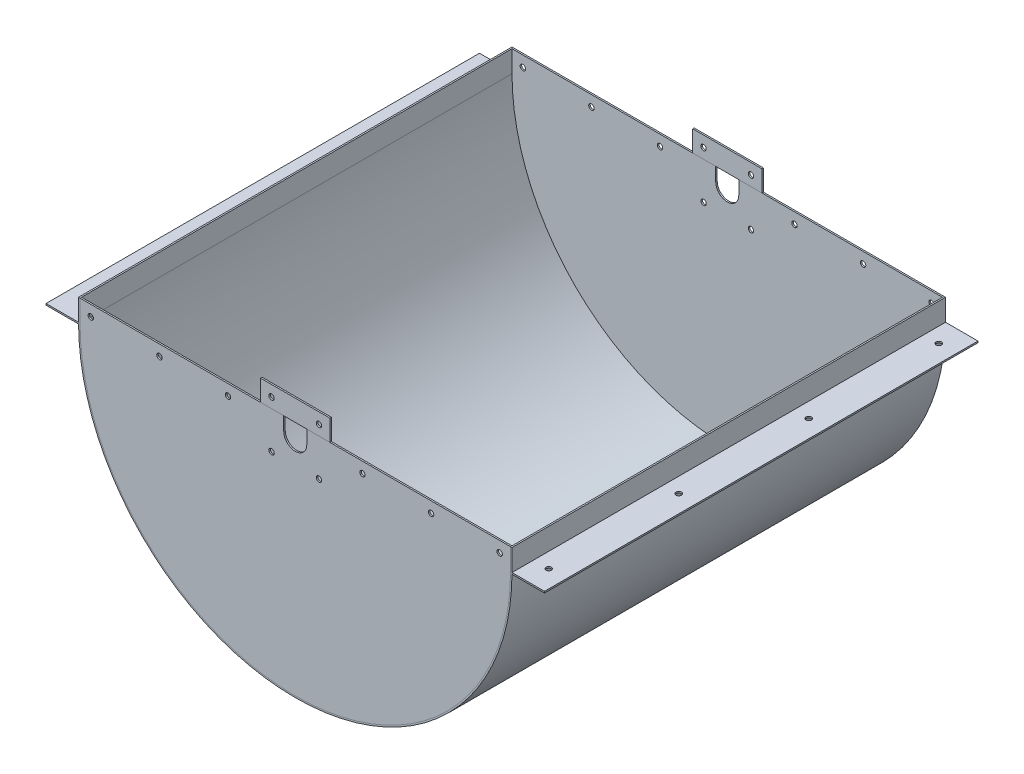
SolidWorks part; units mm, degrees
ref_plane "Plano frontal" through (0, 0, 0) normal (0, 0, 1) x (1, 0, 0)
ref_plane "Plano superior" through (0, 0, 0) normal (0, 1, 0) x (1, 0, 0)
ref_plane "Plano direito" through (0, 0, 0) normal (1, 0, 0) x (0, 0, -1)
sketch "Esboço1" plane through (0, 0, 0) normal (0, 0, 1) x (1, 0, 0)
  line L0 (0, 0) -> (-744.798, 0) construction
  line L1 (0, 0) -> (688.7199, 0) construction
  line L2 (-504.5, 0) -> (-504.5, 50.8)
  line L3 (-504.5, 50.8) -> (-508, 50.8)
  line L4 (-508, 0) -> (-508, 50.8)
  line L5 (0, 0) -> (0, 320.7839) construction
  line L6 (508, 0) -> (508, 50.8)
  line L7 (504.5, 50.8) -> (508, 50.8)
  line L8 (504.5, 0) -> (504.5, 50.8)
  arc A0 (-508, 0) -> (508, 0) centre (0, 0) ccw
  arc A1 (-504.5, 0) -> (504.5, 0) centre (0, 0) ccw
  circle A2 centre (0, 0) radius 508 construction
  circle A3 centre (0, 0) radius 504.5 construction
  dimension "D1" = 1016
  dimension "D3" = 50.8
  dimension "D2" = 3.5
extrude "Ressalto-extrusão1" add sketch "Esboço1" along normal mid plane 1016
sketch "Esboço2" plane through (0, 0, 508) normal (0, 0, 1) x (1, 0, 0)
  line L0 (504.5, 50.8) -> (504.5, 0) construction
  line L1 (-504.5, 0) -> (-504.5, 50.8) construction
  line L2 (504.5, 50.8) -> (504.5, 0)
  line L3 (-504.5, 0) -> (-504.5, 50.8)
  line L4 (-504.5, 50.8) -> (504.5, 50.8)
  arc A0 (-504.5, 0) -> (504.5, 0) centre (0, 0) ccw construction
  arc A1 (-504.5, 0) -> (504.5, 0) centre (0, 0) ccw
extrude "Ressalto-extrusão2" add sketch "Esboço2" against normal blind 3.5 separate body
sketch "Esboço3" plane through (0, 0, 508) normal (0, 0, 1) x (1, 0, 0)
  line L0 (-504.5, 25.4) -> (504.5, 25.4) construction
  line L1 (-504.5, 50.8) -> (-504.5, 0) construction
  line L2 (504.5, 50.8) -> (504.5, 0) construction
  line L3 (504.5, 50.8) -> (-504.5, 50.8) construction
  line L4 (0, 0) -> (0, 166.7118) construction
  line L5 (-504.5, 0) -> (504.5, 0) construction
  line L6 (27, 19.05) -> (27, 50.8)
  line L7 (-27, 19.05) -> (-27, 50.8)
  line L8 (-27, 50.8) -> (27, 50.8)
  circle A0 centre (-479.1, 25.4) radius 6.35
  circle A1 centre (-318.318, 25.4) radius 6.35
  circle A2 centre (-157.536, 25.4) radius 6.35
  arc A3 (-27, 19.05) -> (27, 19.05) centre (0, 19.05) ccw
  circle A4 centre (157.536, 25.4) radius 6.35
  circle A5 centre (318.318, 25.4) radius 6.35
  circle A6 centre (479.1, 25.4) radius 6.35
  dimension "D2" = 12.7
  dimension "D4" = 12.7
  dimension "D5" = 12.7
  dimension "D8" = 54
  dimension "D1" = 25.4
  dimension "D3" = 25.4
  dimension "D6" = 160.782
  dimension "D7" = 160.782
  dimension "D9" = 19.05
extrude "Corte-extrusão1" cut sketch "Esboço3" against normal up to surface (3.5 mm away) up to face at (0, -100.725, 504.5)
sketch "Esboço4" plane through (0, 0, 508) normal (0, 0, 1) x (1, 0, 0)
  line L0 (-27, 50.8) -> (-504.5, 50.8) construction
  line L1 (-80.9625, 50.8) -> (80.9625, 50.8)
  line L2 (-80.9625, 50.8) -> (-80.9625, 99.9998)
  line L3 (-80.9625, 99.9998) -> (80.9625, 99.9998)
  line L4 (80.9625, 50.8) -> (80.9625, 99.9998)
  line L5 (0, 0) -> (0, 239.6694) construction
  line L6 (0, 99.9998) -> (0, 50.8) construction
  dimension "D1" = 161.925
  dimension "D2" = 49.1998
extrude "Ressalto-extrusão3" add sketch "Esboço4" against normal blind 3.5 separate body
sketch "Esboço6" plane through (0, 0, 508) normal (0, 0, 1) x (1, 0, 0)
  line L0 (0, 19.05) -> (0, 97.627) construction
  line L1 (0, 19.05) -> (0, -59.527) construction
  line L2 (0, 19.05) -> (78.577, 19.05) construction
  line L3 (0, 19.05) -> (-78.577, 19.05) construction
  line L4 (0, 19.05) -> (-55.5623, 74.6123) construction
  circle A0 centre (0, 19.05) radius 78.577 construction
  circle A1 centre (-55.5623, 74.6123) radius 6.35
  circle A2 centre (55.5623, 74.6123) radius 6.35
  circle A3 centre (55.5623, -36.5123) radius 6.35
  circle A4 centre (-55.5623, -36.5123) radius 6.35
  point P18 (0, 19.05)
  dimension "D1" = 157.154
  dimension "D3" = 12.7
  dimension "D2" = 45
  dimension "D4" = 4
extrude "Corte-extrusão2" cut sketch "Esboço6" against normal up to surface (3.5 mm away) up to face at (-472.75, 25.4, 504.5)
mirror "Espelhar1" about plane through (0, 0, 0) normal (0, 0, 1) of bodies 105 106
sketch "Esboço7" plane through (0, 0, 0) normal (0, 1, 0) x (1, 0, 0)
  line L0 (504.5, 508) -> (27, 508) construction
  line L1 (508, -508) -> (584.2, -508)
  line L2 (508, -508) -> (508, 508)
  line L3 (508, 508) -> (584.2, 508)
  line L4 (584.2, -508) -> (584.2, 508)
  dimension "D1" = 76.2
extrude "Ressalto-extrusão4" add sketch "Esboço7" against normal blind 3.5 separate body
mirror "Espelhar2" about plane through (0, 0, 0) normal (1, 0, 0) of bodies 109
sketch "Esboço8" plane through (0, 0, 0) normal (0, 1, 0) x (1, 0, 0)
  line L0 (-565.65, -152.401) -> (-520.85, -152.401) construction
  line L1 (-520.85, 152.401) -> (-565.65, 152.401) construction
  line L2 (0, 0) -> (0, 1051.6795) construction
  circle A0 centre (-543.25, -457.2) radius 6.35
  circle A1 centre (-543.25, -152.401) radius 6.351
  circle A2 centre (-543.25, 152.401) radius 6.351
  circle A3 centre (-543.25, 457.2) radius 6.35
  circle A4 centre (543.25, 457.2) radius 6.35
  circle A5 centre (543.25, 152.401) radius 6.351
  circle A6 centre (543.25, -152.401) radius 6.351
  circle A7 centre (543.25, -457.2) radius 6.35
  dimension "D1" = 12.7
  dimension "D2" = 12.702
  dimension "D3" = 12.702
  dimension "D4" = 12.7
extrude "Corte-extrusão3" cut sketch "Esboço8" against normal up to surface (3.5 mm away) up to face at (-546.1, -3.5, 0)
equation "\"D4@Esboço3\"=\"D2@Esboço3\""
equation "\"D7@Esboço3\"=\"D6@Esboço3\""
equation "\"D5@Esboço3\"=\"D4@Esboço3\""
